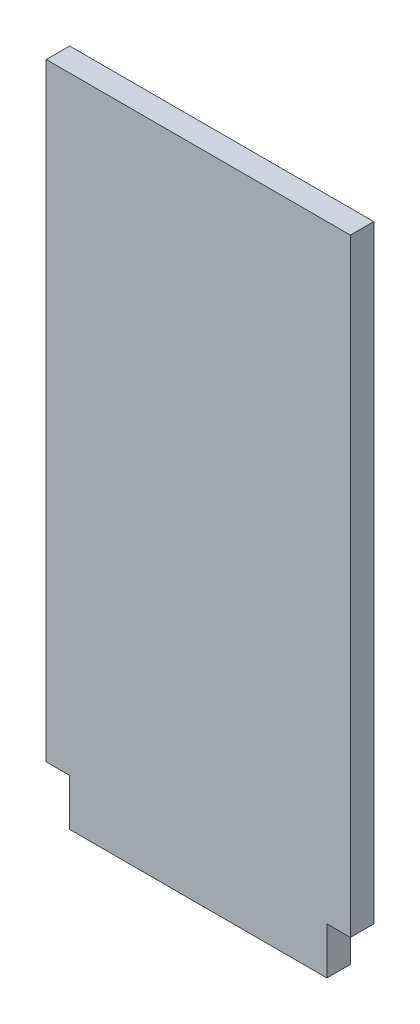
SolidWorks part; units mm, degrees
material "Thornel Mat VMA"
ref_plane "前视" through (0, 0, 0) normal (0, 0, 1) x (1, 0, 0)
ref_plane "上视" through (0, 0, 0) normal (0, 1, 0) x (1, 0, 0)
ref_plane "右视" through (0, 0, 0) normal (1, 0, 0) x (0, 0, -1)
sketch "草图1" plane through (0, 0, 0) normal (0, 0, 1) x (1, 0, 0)
  line L0 (0, -73.8423) -> (0, -45.6387) construction
  line L1 (27.5, -70) -> (-27.5, -70)
  line L2 (32.5, -60) -> (32.5, 70)
  line L3 (32.5, 70) -> (-32.5, 70)
  line L4 (-32.5, -60) -> (-32.5, 70)
  line L5 (32.5, -70) -> (-32.5, 70) construction
  line L6 (32.5, 70) -> (-32.5, -70) construction
  line L7 (-27.5, -70) -> (-27.5, -60)
  line L8 (-27.5, -60) -> (-32.5, -60)
  line L9 (27.5, -70) -> (27.5, -60)
  line L10 (27.5, -60) -> (32.5, -60)
  point P0 (0, 0)
  dimension "D1" = 140
  dimension "D2" = 65
  dimension "D3" = 10
  dimension "D4" = 5
extrude "凸台-拉伸1" add sketch "草图1" along normal blind 5
sketch "草图2" plane through (0, 0, 5) normal (0, 0, 1) x (1, 0, 0)
  line L0 (0, -71.2105) -> (0, 70.6556)
sketch "草图3" plane through (0, 70, 0) normal (0, 1, 0) x (1, 0, 0)
  line L0 (0, -5) -> (0, 0)
  line L1 (32.5, -5) -> (-32.5, -5) construction
  line L2 (32.5, 0) -> (-32.5, 0) construction
